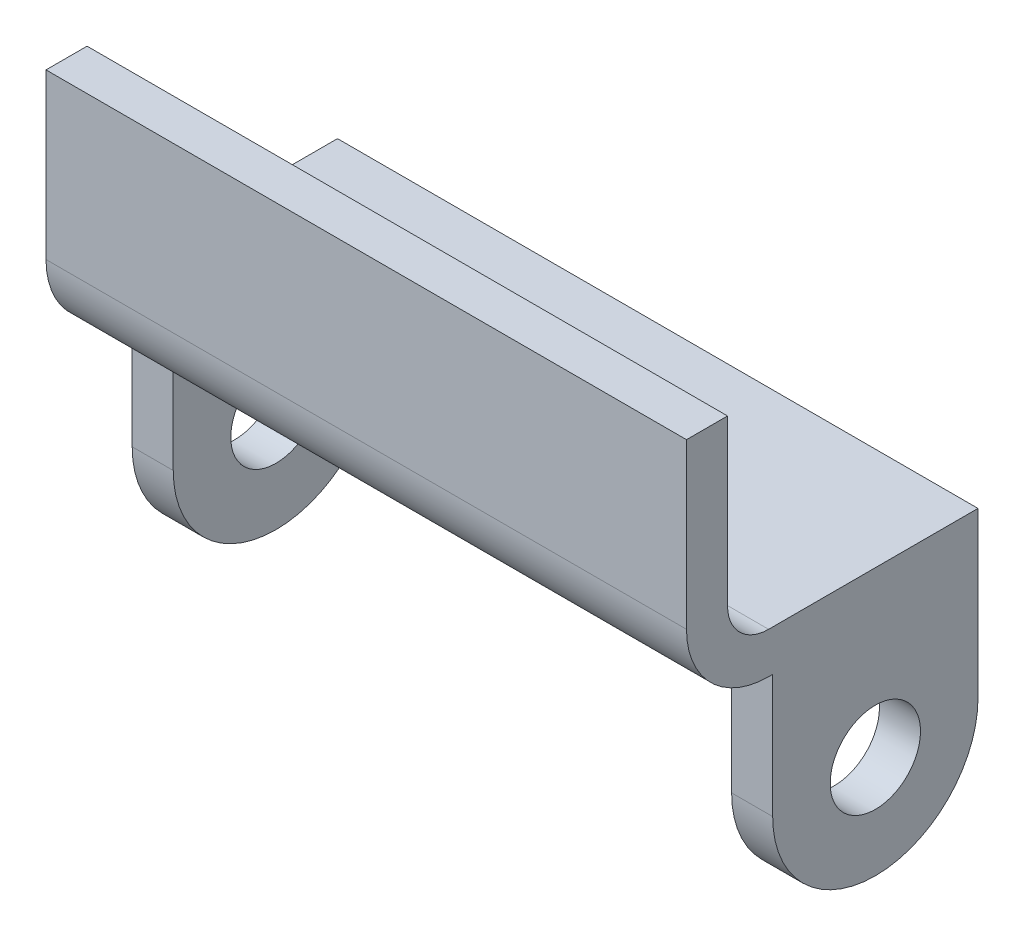
SolidWorks part; units mm, degrees
material "AISI 4130 Steel, normalized at 870C"
ref_plane "Front Plane" through (0, 0, 0) normal (1, 0, 0) x (0, 1, 0)
ref_plane "Top Plane" through (0, 0, 0) normal (0, 0, 1) x (0, 1, 0)
ref_plane "Right Plane" through (0, 0, 0) normal (0, 1, 0) x (-1, 0, 0)
sketch "Sketch1" plane through (0, 0, 0) normal (1, 0, 0) x (0, 1, 0)
  line L0 (-156.6359, -84.5934) -> (-176.6359, -84.5934)
  line L1 (-181.6359, -89.5934) -> (-181.6359, -115.0934)
  line L3 (-156.6359, -79.5934) -> (-176.6359, -79.5934)
  line L4 (-186.6359, -89.5934) -> (-186.6359, -115.0934)
  line L5 (-156.6359, -84.5934) -> (-156.6359, -79.5934)
  line L6 (-181.6359, -115.0934) -> (-186.6359, -115.0934)
  circle A0 centre (-164.1359, -102.0934) radius 17.5
  arc A1 (-151.3986, -90.0929) -> (-148.4541, -109.8607) centre (-164.1359, -102.0934) ccw construction
  arc A2 (-176.6359, -84.5934) -> (-181.6359, -89.5934) centre (-176.6359, -89.5934) ccw
  arc A3 (-176.6359, -79.5934) -> (-186.6359, -89.5934) centre (-176.6359, -89.5934) ccw
  point P16 (-184.1359, -115.0934)
  dimension "D1" = 35
  dimension "D2" = 5
  dimension "D3" = 20
  dimension "D5" = 13
  dimension "D4" = 5
extrude "Boss-Extrude1" add sketch "Sketch1" along normal mid plane 78 contours L3 A3 L4 L6 L1 A2 L0 L5
sketch "Sketch3" plane through (39, 0, 0) normal (1, 0, 0) x (0, 1, 0)
  line L1 (-181.6359, -115.0934) -> (-201.6359, -115.0934)
  line L2 (-181.6359, -115.0934) -> (-181.6359, -90.0888)
  line L3 (-181.6359, -90.0888) -> (-201.6359, -90.0888)
  arc A0 (-201.6359, -90.0888) -> (-201.6359, -115.0934) centre (-201.6359, -102.5911) ccw
  circle A1 centre (-201.6359, -102.5911) radius 5.5
  dimension "D2" = 11
  dimension "D1" = 20
  dimension "D3" = 25.0046
extrude "Boss-Extrude2" add sketch "Sketch3" against normal blind 5
mirror "Mirror1" about plane through (0, 0, 0) normal (1, 0, 0) of "Boss-Extrude2"
sketch "Sketch4" plane through (0, 0, -79.5934) normal (0, 0, 1) x (1, 0, 0)
  line L0 (39, -156.6359) -> (-39, -156.6359) construction
  line L1 (39, -156.6359) -> (39, -176.6359) construction
  circle A0 centre (28, -166.6359) radius 3
  dimension "D1" = 6
  dimension "D2" = 10
  dimension "D3" = 11
extrude "Cut-Extrude1" [suppressed] cut sketch "Sketch4" against normal through all both and the other way through all
mirror "Mirror2" [suppressed] about plane through (0, 0, 0) normal (1, 0, 0)
